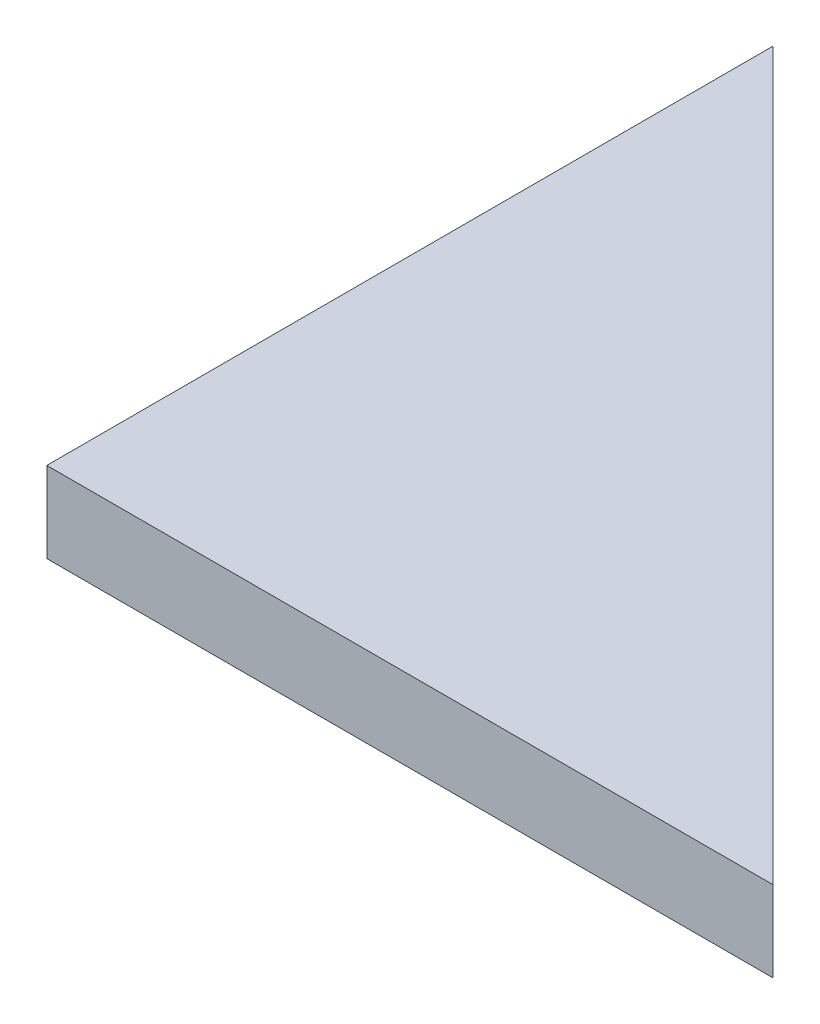
SolidWorks part; units mm, degrees
material "Galvanized Steel"
ref_plane "Front Plane" through (0, 0, 0) normal (0, 0, 1) x (1, 0, 0)
ref_plane "Top Plane" through (0, 0, 0) normal (0, 1, 0) x (1, 0, 0)
ref_plane "Right Plane" through (0, 0, 0) normal (1, 0, 0) x (0, 0, -1)
sketch "Sketch1" plane through (0, 0, 0) normal (0, 1, 0) x (1, 0, 0)
  line L0 (0, 0) -> (57.15, 0)
  line L1 (0, 0) -> (0, 57.15)
  line L2 (0, 57.15) -> (57.15, 0)
  dimension "D1" = 57.15
extrude "Gusset" add sketch "Sketch1" along normal mid plane 6.35
